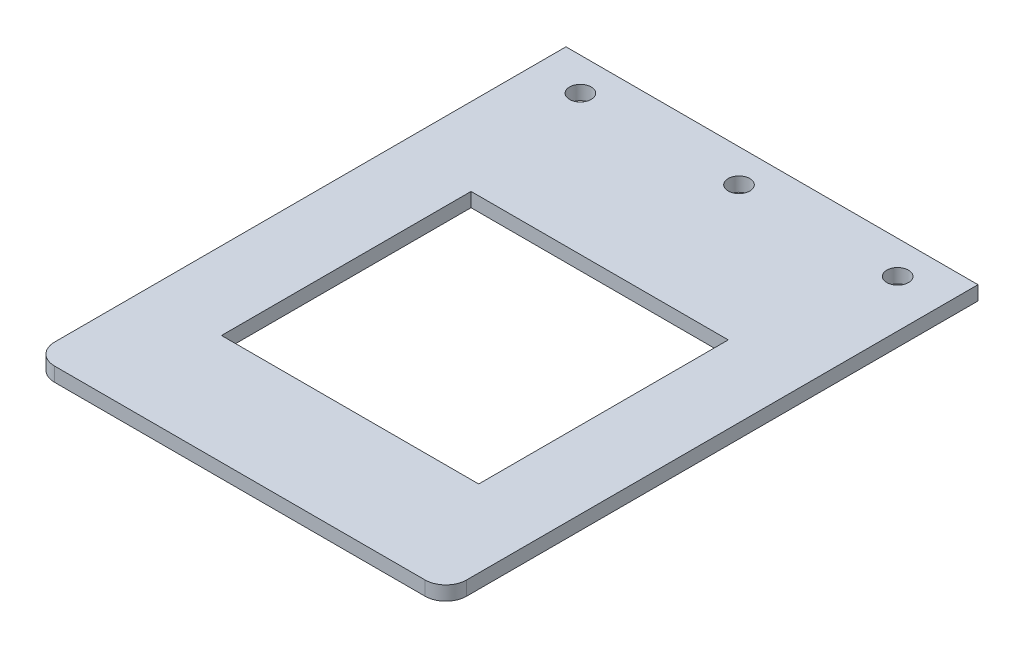
SolidWorks part; units mm, degrees
ref_plane "Front Plane" through (0, 0, 0) normal (0, 0, 1) x (1, 0, 0)
ref_plane "Top Plane" through (0, 0, 0) normal (0, 1, 0) x (1, 0, 0)
ref_plane "Right Plane" through (0, 0, 0) normal (1, 0, 0) x (0, 0, -1)
sketch "Sketch1" plane through (0, 0, 0) normal (0, 1, 0) x (1, 0, 0)
  line L10 (-16.9379, -16.3429) -> (10.3671, -16.3429)
  line L11 (10.3671, -16.3429) -> (10.3671, 10.1491)
  line L12 (10.3671, 10.1491) -> (-16.9379, 10.1491)
  line L13 (-16.9379, 10.1491) -> (-16.9379, -16.3429)
  line L16 (-14.2871, 14.6854) -> (12.9539, 14.6854)
  line L17 (12.9539, 14.6854) -> (12.9539, 18.4324)
  line L18 (12.9539, 18.4324) -> (-14.2871, 18.4324)
  line L19 (-14.2871, 18.4324) -> (-14.2871, 14.6854)
  line L22 (-25.1937, -23.3118) -> (-25.1937, 28.4832)
  line L23 (18.5453, 28.4832) -> (18.5453, -23.3118)
  line L24 (-25.1937, 28.4832) -> (18.5453, 28.4832)
  line L25 (18.5453, -23.3118) -> (18.5453, -24.5118)
  line L26 (-25.1937, -23.3118) -> (-25.1937, -24.5118)
  line L27 (18.5453, -24.5118) -> (18.5453, -25.8118)
  line L30 (-25.1937, -24.5118) -> (-25.1937, -25.8118)
  line L32 (-22.9937, -28.0118) -> (16.3453, -28.0118)
  circle A0 centre (-20.1649, 24.9832) radius 1.15
  circle A1 centre (-3.3249, 24.9832) radius 1.15
  circle A2 centre (13.5151, 24.9832) radius 1.15
  arc A7 (18.5453, -25.8118) -> (16.3453, -28.0118) centre (16.3453, -25.8118) cw
  arc A8 (-25.1937, -25.8118) -> (-22.9937, -28.0118) centre (-22.9937, -25.8118) ccw
extrude "Boss-Extrude1" add sketch "Sketch1" along normal blind 1.5
sketch "Sketch2" plane through (0, 1.5, 0) normal (0, 1, 0) x (1, 0, 0)
  line L0 (-14.2871, 18.4324) -> (12.9539, 18.4324)
  line L1 (12.9539, 18.4324) -> (12.9539, 14.6854)
  line L2 (12.9539, 14.6854) -> (-14.2871, 14.6854)
  line L3 (-14.2871, 14.6854) -> (-14.2871, 18.4324)
  line L4 (18.5453, 28.4832) -> (-25.1937, 28.4832)
  line L5 (-25.1937, 28.4832) -> (-25.1937, -25.8118)
  line L6 (-22.9937, -28.0118) -> (16.3453, -28.0118)
  line L7 (18.5453, -25.8118) -> (18.5453, 28.4832)
  line L8 (18.5453, 28.4832) -> (-25.1937, 28.4832)
  line L9 (-25.1937, 28.4832) -> (-25.1937, -25.8118)
  line L11 (18.5453, -25.8118) -> (18.5453, 28.4832)
  line L17 (-22.9937, -28.0118) -> (16.3453, -28.0118)
  arc A2 (-25.1937, -25.8118) -> (-22.9937, -28.0118) centre (-22.9937, -25.8118) ccw
  arc A6 (-25.1937, -25.8118) -> (-22.9937, -28.0118) centre (-22.9937, -25.8118) ccw
  arc A8 (16.3453, -28.0118) -> (18.5453, -25.8118) centre (16.3453, -25.8118) ccw
  arc A9 (16.3453, -28.0118) -> (18.5453, -25.8118) centre (16.3453, -25.8118) ccw
  dimension "D1" = 0
extrude "Boss-Extrude2" add sketch "Sketch2" along normal blind 2 separate body contours L3 L0 L1 L2
sketch "Sketch3" plane through (0, 1.5, 0) normal (0, -1, 0) x (1, 0, 0)
  line L4 (12.9539, -14.6854) -> (-14.2871, -14.6854)
  line L5 (-14.2871, -14.6854) -> (-14.2871, -18.4324)
  line L6 (-14.2871, -18.4324) -> (12.9539, -18.4324)
  line L7 (12.9539, -18.4324) -> (12.9539, -14.6854)
  line L8 (12.9539, -14.6854) -> (-14.2871, -14.6854)
  line L9 (-14.2871, -14.6854) -> (-14.2871, -18.4324)
  line L10 (-14.2871, -18.4324) -> (12.9539, -18.4324)
  line L11 (12.9539, -18.4324) -> (12.9539, -14.6854)
  dimension "D1" = 0
extrude "Boss-Extrude3" add sketch "Sketch3" along normal up to surface (1.5 mm away) up to face at (-3.3249, 0, -23.8332)
sketch "Sketch5" plane through (0, 0, 0) normal (0, -1, 0) x (1, 0, 0)
  line L0 (-14.2871, -18.4324) -> (-9.2871, -18.4324)
  line L1 (-9.2871, -18.4324) -> (-9.2871, -14.6854)
  line L2 (12.9539, -18.4324) -> (7.9539, -18.4324)
  line L3 (7.9539, -18.4324) -> (7.9539, -14.6854)
  line L4 (12.9539, -14.6854) -> (-14.2871, -14.6854)
  line L5 (12.9539, -18.4324) -> (12.9539, -14.6854)
  line L6 (-14.2871, -18.4324) -> (12.9539, -18.4324)
  line L7 (-14.2871, -14.6854) -> (-14.2871, -18.4324)
  line L8 (12.9539, -14.6854) -> (-14.2871, -14.6854)
  line L9 (12.9539, -18.4324) -> (12.9539, -14.6854)
  line L10 (-14.2871, -18.4324) -> (12.9539, -18.4324)
  line L11 (-14.2871, -14.6854) -> (-14.2871, -18.4324)
  line L12 (7.9539, -14.6854) -> (-9.2871, -14.6854)
  line L13 (-9.2871, -18.4324) -> (7.9539, -18.4324)
  dimension "D1" = 0
extrude "Boss-Extrude4" add sketch "Sketch5" along normal blind 3 contours L1 L10 L3 L8
sketch "Sketch6" plane through (0, 3.5, 0) normal (0, 1, 0) x (1, 0, 0)
  line L4 (-14.2871, 14.6854) -> (12.9539, 14.6854)
  line L5 (12.9539, 14.6854) -> (12.9539, 18.4324)
  line L6 (12.9539, 18.4324) -> (-14.2871, 18.4324)
  line L7 (-14.2871, 18.4324) -> (-14.2871, 14.6854)
  line L8 (-14.2871, 14.6854) -> (12.9539, 14.6854)
  line L9 (12.9539, 14.6854) -> (12.9539, 18.4324)
  line L10 (12.9539, 18.4324) -> (-14.2871, 18.4324)
  line L11 (-14.2871, 18.4324) -> (-14.2871, 14.6854)
  dimension "D1" = 0
extrude "Cut-Extrude1" cut sketch "Sketch6" against normal up to surface (2 mm away) up to face at (-0.6666, 1.5, -16.5589)
